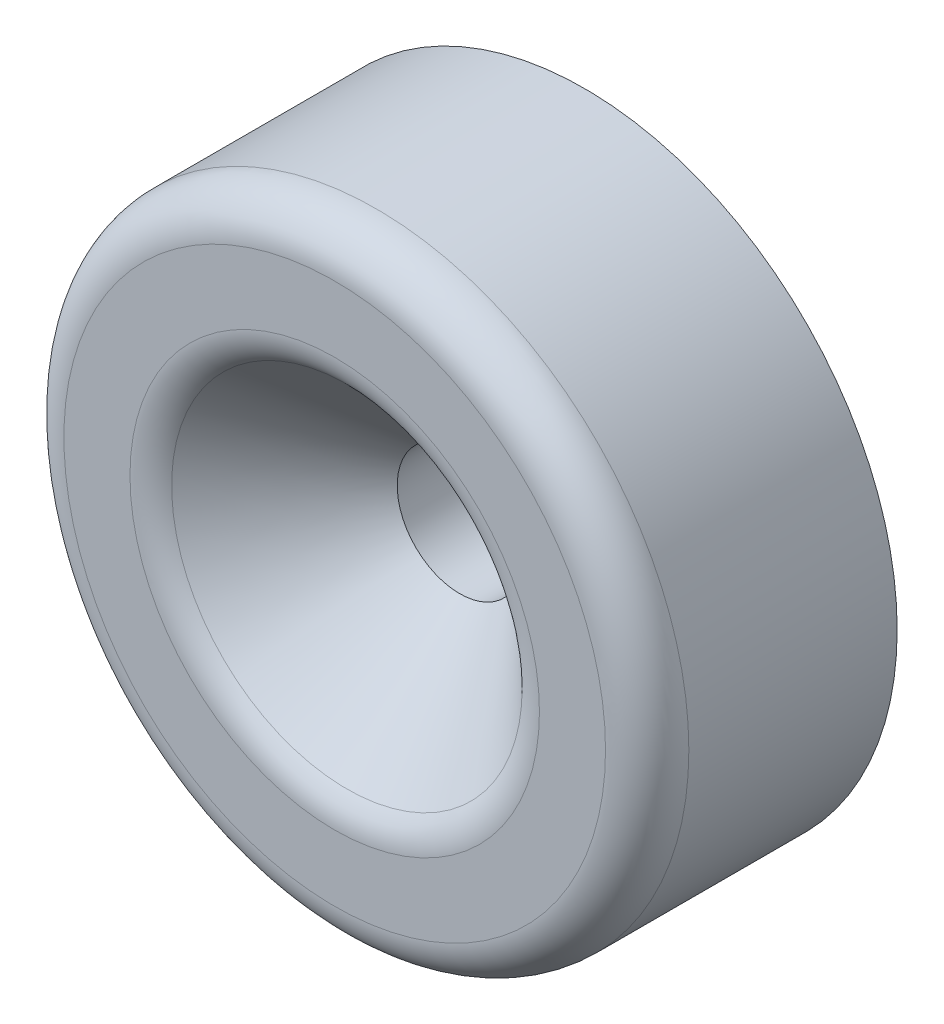
SolidWorks part; units mm, degrees
ref_plane "Front" through (0, 0, 0) normal (0, 0, 1) x (1, 0, 0)
ref_plane "Top" through (0, 0, 0) normal (0, 1, 0) x (1, 0, 0)
ref_plane "Right" through (0, 0, 0) normal (1, 0, 0) x (0, 0, -1)
sketch "Esquisse1" plane through (0, 0, 0) normal (0, 0, 1) x (1, 0, 0)
  circle A0 centre (0, 0) radius 3
  circle A1 centre (0, 0) radius 15
  dimension "D1" = 6
  dimension "D2" = 30
extrude "Boss.-Extru.1" add sketch "Esquisse1" along normal blind 12
chamfer "Chanfrein1" distance 6 angle 45 1 edges at (3, 0, 12)
fillet "Congé1" radius 2 2 edges at (15, 0, 12) (9, 0, 12)
